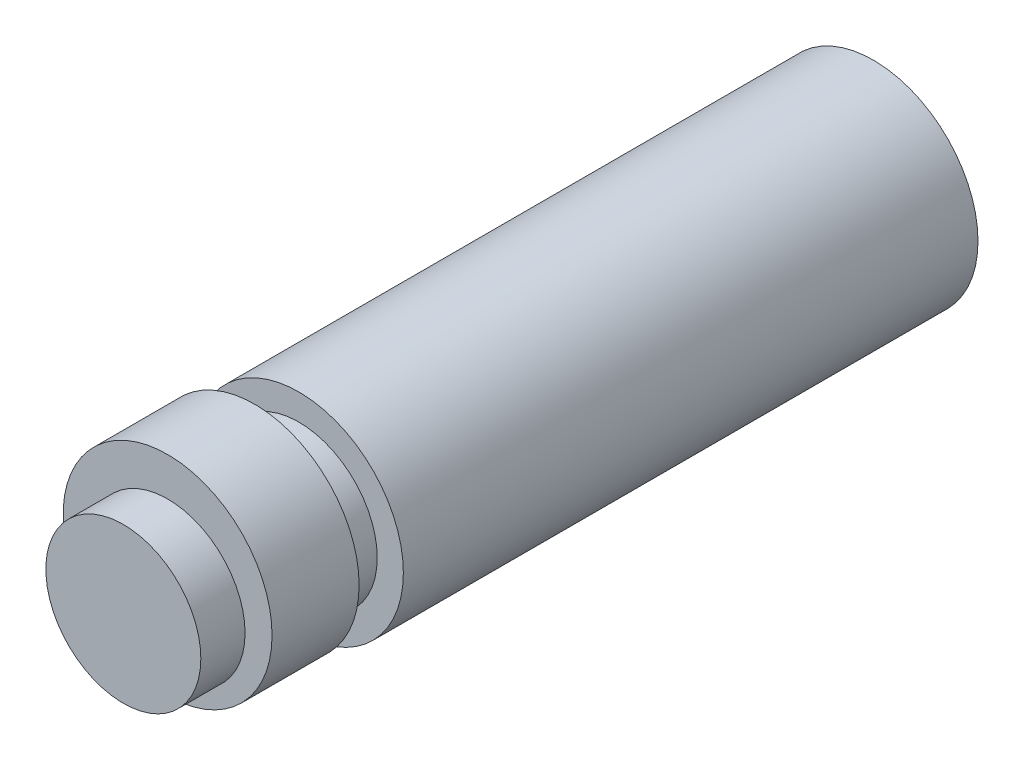
SolidWorks part; units mm, degrees
material "ABS"
ref_plane "Front Plane" through (0, 0, 0) normal (0, 0, 1) x (1, 0, 0)
ref_plane "Top Plane" through (0, 0, 0) normal (0, 1, 0) x (1, 0, 0)
ref_plane "Right Plane" through (0, 0, 0) normal (1, 0, 0) x (0, 0, -1)
sketch "Sketch1" plane through (0, 0, 0) normal (0, 0, 1) x (1, 0, 0)
  circle A0 centre (0, 0) radius 6
  dimension "D1" = 12
extrude "Boss-Extrude1" add sketch "Sketch1" along normal blind 33
sketch "Sketch7" plane through (0, 0, 33) normal (0, 0, 1) x (1, 0, 0)
  circle A0 centre (0, 0) radius 4.5
  dimension "D1" = 9
extrude "Boss-Extrude7" add sketch "Sketch7" along normal blind 2.54
sketch "Sketch2" plane through (0, 0, 33) normal (0, 0, 1) x (1, 0, 0)
  line L0 (-5.8641, 1.27) -> (-8.2333, -9.6697)
  line L1 (0, 0) -> (0, 3.8494) construction
  line L2 (5.8641, 1.27) -> (8.2333, -9.6697)
  line L3 (-5.8641, 1.27) -> (5.8641, 1.27)
  line L4 (0, -12.7) -> (0, 0) construction
  circle A0 centre (0, 0) radius 6 construction
  arc A1 (-8.2333, -9.6697) -> (8.2333, -9.6697) centre (0, 0) ccw
  dimension "D1" = 1.27
  dimension "D2" = 12.7
extrude "Boss-Extrude2" [suppressed] add sketch "Sketch2" against normal blind 2.54
sketch "Sketch3" plane through (0, 0, 35.54) normal (0, 0, 1) x (1, 0, 0)
  circle A0 centre (0, 0.6604) radius 6
  circle A1 centre (0, 0) radius 6
  circle A2 centre (0, 0) radius 6 construction
  dimension "D3" = 12
  dimension "D2" = 0.6604
  dimension "D1" = 0
extrude "Boss-Extrude3" add sketch "Sketch3" along normal blind 5
sketch "Sketch6" plane through (0, 0, 40.54) normal (0, 0, 1) x (1, 0, 0)
  circle A0 centre (0, -2.54) radius 5.08
  dimension "D1" = 10.16
  dimension "D2" = 2.54
extrude "Boss-Extrude6" [suppressed] add sketch "Sketch6" along normal blind 2.54
sketch "Sketch4" plane through (0, 0, 40.54) normal (0, 0, 1) x (1, 0, 0)
  circle A0 centre (0, 0) radius 4.45
  dimension "D1" = 8.9
extrude "Boss-Extrude4" add sketch "Sketch4" along normal blind 2.54
sketch "Sketch5" plane through (0, 0, 0) normal (0, 0, -1) x (-1, 0, 0)
  line L1 (-1.075, 3.9825) -> (1.075, 3.9825)
  line L2 (-1.075, 3.9825) -> (-1.075, 5.0925)
  line L3 (-1.075, 5.0925) -> (1.075, 5.0925)
  line L4 (1.075, 3.9825) -> (1.075, 5.0925)
  circle A2 centre (0, 0) radius 4.125
  point P4 (0, 3.9825)
  dimension "D1" = 8.25
  dimension "D2" = 1.11
  dimension "D3" = 2.15
extrude "Cut-Extrude1" cut sketch "Sketch5" against normal blind 31.5 contours A2 L4 L3 L2 | L4 A2 L2 L1 | L2 A2 L4 L1
